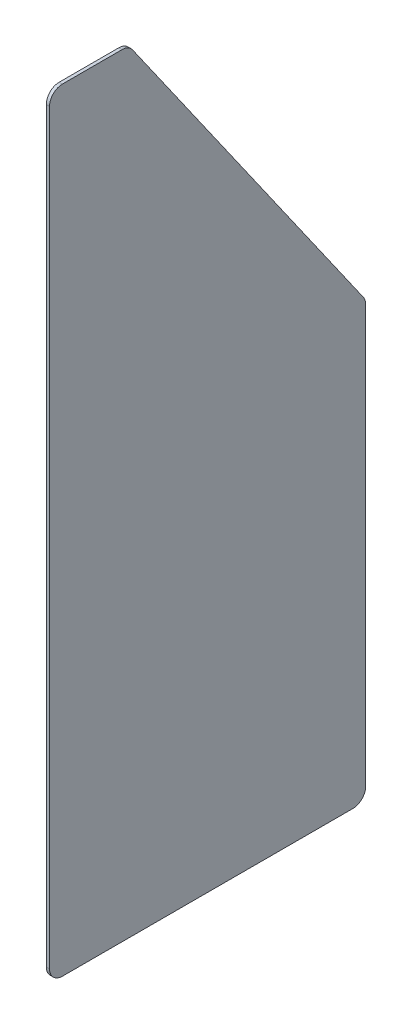
SolidWorks part; units mm, degrees
material "PC High Viscosity"
ref_plane "Front Plane" through (0, 0, 0) normal (0, 0, 1) x (1, 0, 0)
ref_plane "Top Plane" through (0, 0, 0) normal (0, 1, 0) x (1, 0, 0)
ref_plane "Right Plane" through (0, 0, 0) normal (1, 0, 0) x (0, 0, -1)
sketch "Sketch1" plane through (0, 0, 0) normal (0, 1, 0) x (1, 0, 0)
  line L4 (1.5875, 155.8925) -> (0, 155.8925)
  line L5 (0, 155.8925) -> (0, 0)
  line L6 (1.5875, 155.8925) -> (1.5875, 0)
  line L7 (1.5875, 0) -> (0, 0)
  dimension "D1" = 155.8925
  dimension "D4" = 1.5875
extrude "Boss-Extrude1" add sketch "Sketch1" along normal blind 381
sketch "Sketch2" plane through (0, 0, 0) normal (-1, 0, 0) x (0, 0, 1)
  line L0 (-39.0525, 381) -> (-155.8925, 214.122)
  line L1 (-155.8925, 214.122) -> (-155.8925, 381)
  line L2 (-155.8925, 381) -> (-39.0525, 381)
  line L3 (-155.8925, 381) -> (-155.8925, 0) construction
  line L4 (-155.8925, 381) -> (0, 381) construction
  line L5 (0, 381) -> (0, 0) construction
  dimension "D1" = 214.122
  dimension "D2" = 39.0525
extrude "Cut-Extrude1" cut sketch "Sketch2" against normal up to surface (1.5875 mm away) up to face at (1.5875, 190.5, -77.9462)
fillet "Fillet1" radius 6.35 5 edges at (0.7937, 0, -155.8925) (0.7938, 0, 0) (0.7938, 381, 0) (0.7937, 381, -39.0525) (0.7937, 214.122, -155.8925)
